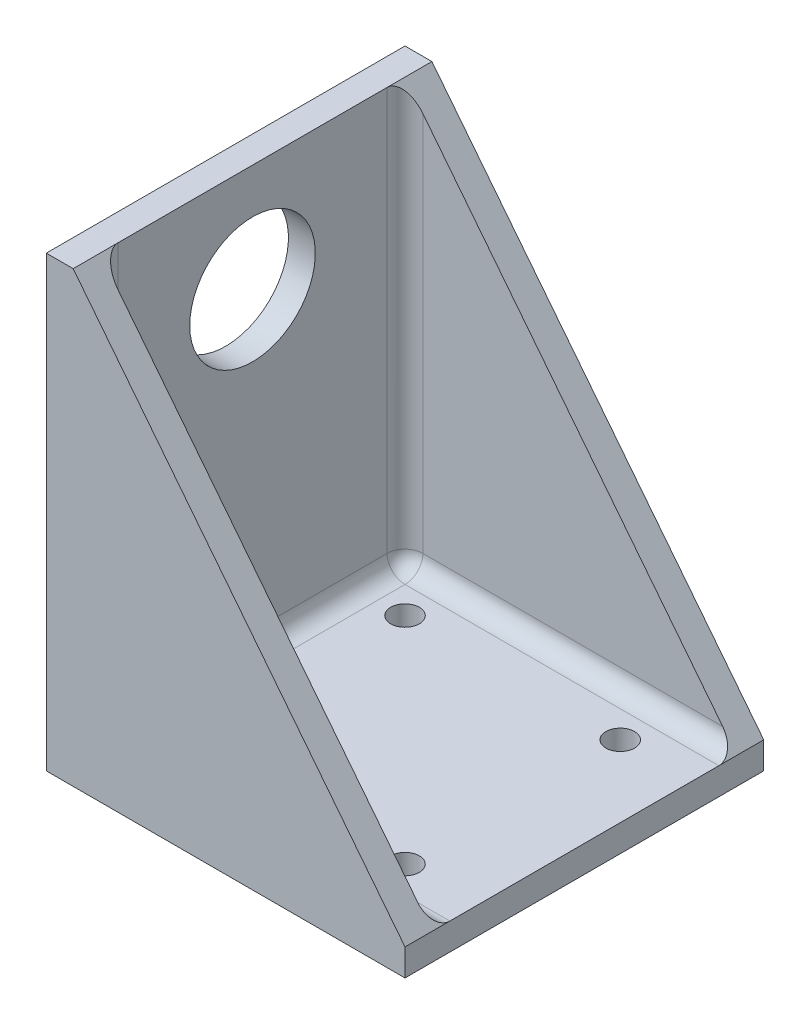
SolidWorks part; units mm, degrees
ref_plane "Front Plane" through (0, 0, 0) normal (0, 0, 1) x (1, 0, 0)
ref_plane "Top Plane" through (0, 0, 0) normal (0, 1, 0) x (1, 0, 0)
ref_plane "Right Plane" through (0, 0, 0) normal (1, 0, 0) x (0, 0, -1)
sketch "Sketch3" plane through (0, 0, 0) normal (0, 1, 0) x (1, 0, 0)
  line L0 (-20, 0) -> (20, 0) construction
  line L1 (-20, -20) -> (20, -20)
  line L2 (-20, -20) -> (-20, 20)
  line L3 (-20, 20) -> (20, 20)
  line L4 (20, -20) -> (20, 20)
  line L5 (-20, -20) -> (20, 20) construction
  line L6 (-20, 20) -> (20, -20) construction
  line L7 (0, 20) -> (0, -20) construction
  circle A0 centre (-12, 12) radius 1.6
  circle A1 centre (-12, -12) radius 1.6
  circle A2 centre (12, -12) radius 1.6
  circle A3 centre (12, 12) radius 1.6
  point P0 (0, 0)
  dimension "D1" = 3.2
  dimension "D2" = 12
  dimension "D3" = 8
  dimension "D4" = 8
  dimension "D5" = 12
extrude "Boss-Extrude2" add sketch "Sketch3" along normal blind 3
sketch "Sketch4" plane through (-20, 0, 0) normal (-1, 0, 0) x (0, 0, 1)
  line L1 (-20, 0) -> (20, 0)
  line L2 (-20, 0) -> (-20, 50)
  line L3 (-20, 50) -> (20, 50)
  line L4 (20, 0) -> (20, 50)
  circle A0 centre (0, 38) radius 7
  point P7 (20, 0)
  dimension "D2" = 14
  dimension "D1" = 50
  dimension "D3" = 12
extrude "Boss-Extrude3" add sketch "Sketch4" against normal blind 3
sketch "Sketch5" plane through (0, 0, 20) normal (0, 0, 1) x (1, 0, 0)
  line L0 (-20, 50) -> (-17, 50)
  line L1 (-17, 50) -> (20, 3)
  line L2 (-17, 3) -> (20, 3) construction
  line L3 (20, 3) -> (20, 0) construction
  line L4 (20, 3) -> (20, 0)
  line L5 (20, 0) -> (-20, 0)
  line L6 (-20, 0) -> (-20, 50)
extrude "Boss-Extrude4" add sketch "Sketch5" against normal blind 3
ref_plane "Plane2" through (0, 0, 0) normal (0, 0, 1) x (1, 0, 0)
mirror "Mirror1" about plane through (0, 0, 0) normal (0, 0, 1) of "Boss-Extrude4"
fillet "Fillet1" radius 2 5 edges at (1.5, 3, 17) (1.5, 3, -17) (-17, 3, 0) (-17, 26.5, -17) (-17, 26.5, 17)
